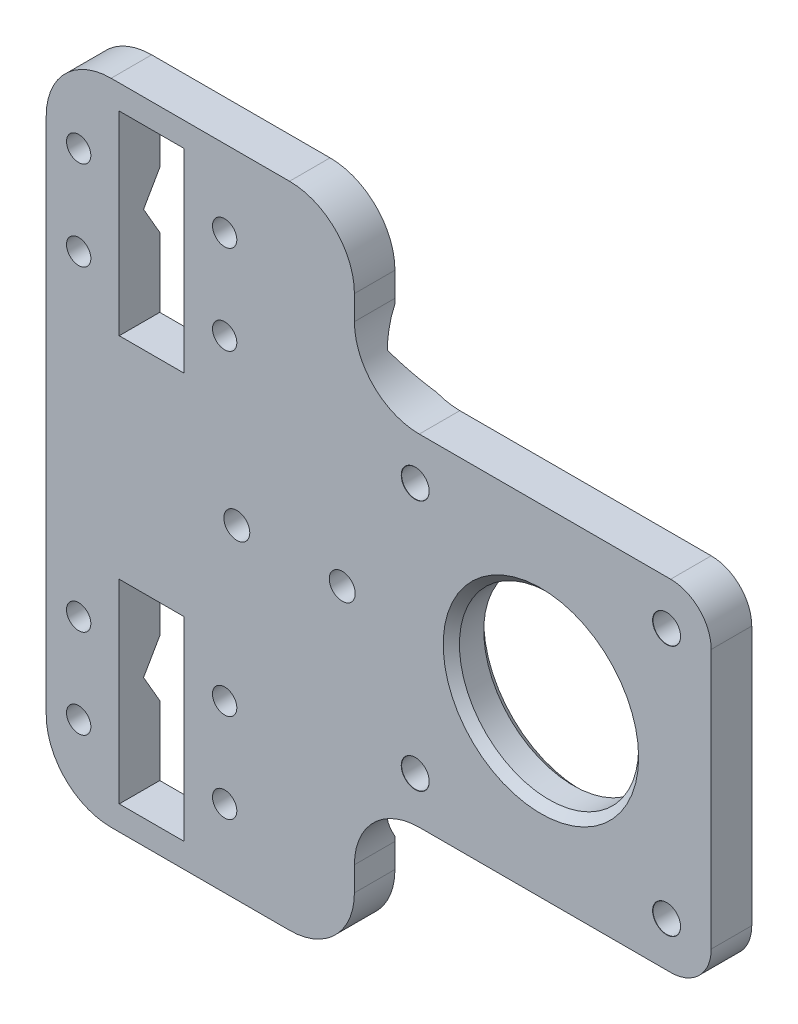
SolidWorks part; units mm, degrees
material "Liga 1060"
ref_plane "Plano frontal" through (0, 0, 0) normal (0, 0, 1) x (1, 0, 0)
ref_plane "Plano superior" through (0, 0, 0) normal (0, 1, 0) x (1, 0, 0)
ref_plane "Plano direito" through (0, 0, 0) normal (1, 0, 0) x (0, 0, -1)
sketch "Esboço1" plane through (0, 0, 0) normal (0, 0, 1) x (1, 0, 0)
  line L0 (0, 0) -> (41, 0) construction
  line L1 (-41, 40) -> (41, 40)
  line L2 (-41, 40) -> (-41, -40)
  line L3 (-41, -40) -> (41, -40)
  line L4 (41, 40) -> (41, -40)
  line L5 (-41, 40) -> (41, -40) construction
  line L6 (-41, -40) -> (41, 40) construction
  line L7 (-32, 37) -> (-24, 37)
  line L8 (-32, 37) -> (-32, 13)
  line L9 (-32, 13) -> (-24, 13)
  line L10 (-24, 37) -> (-24, 13)
  line L11 (-32, 37) -> (-24, 13) construction
  line L12 (-32, 13) -> (-24, 37) construction
  line L13 (-32, -13) -> (-24, -37) construction
  line L14 (-32, -37) -> (-24, -13) construction
  line L15 (-24, -37) -> (-24, -13)
  line L16 (-32, -13) -> (-24, -13)
  line L17 (-32, -37) -> (-32, -13)
  line L18 (-32, -37) -> (-24, -37)
  line L19 (-28, 25) -> (-32, 25) construction
  line L21 (-28, 25) -> (-28, 13) construction
  line L22 (-38.9278, 25) -> (-18.8884, 25) construction
  circle A0 centre (-37, 19.5) radius 1.5
  circle A1 centre (-37, -19.5) radius 1.5
  circle A2 centre (-19, -19.5) radius 1.5
  circle A3 centre (-19, 19.5) radius 1.5
  circle A4 centre (-19, 30.5) radius 1.5
  circle A5 centre (-37, 30.5) radius 1.5
  circle A6 centre (-37, -30.5) radius 1.5
  circle A7 centre (-19, -30.5) radius 1.5
  point P0 (0, 0)
  point P5 (-28, 25)
  point P17 (-28, -25)
  dimension "D7" = 3
  dimension "D8" = 9
  dimension "D9" = 5.5
  dimension "D1" = 80
  dimension "D2" = 82
  dimension "D3" = 8
  dimension "D4" = 24
  dimension "D5" = 25
  dimension "D6" = 13
extrude "Ressalto-extrusão1" add sketch "Esboço1" along normal blind 5
sketch "Esboço2" plane through (41, 0, 0) normal (1, 0, 0) x (0, 0, -1)
  line L0 (0, 25) -> (-2, 25) construction
  line L1 (0, -40) -> (0, 40) construction
  line L2 (-2, 25) -> (0, 28.4641)
  line L3 (0, 28.4641) -> (0, 21.5359)
  line L4 (-2, 25) -> (0, 21.5359)
  line L5 (0, 0) -> (-5, 0) construction
  line L6 (-5, -40) -> (-5, 40) construction
  line L7 (0, -25) -> (-2, -25) construction
  line L8 (-2, -25) -> (0, -21.5359)
  line L9 (0, -28.4641) -> (0, -21.5359)
  line L10 (-2, -25) -> (0, -28.4641)
  line L11 (0, 37) -> (0, 13) construction
  circle A0 centre (2.6188, 25) radius 4 construction
  point P17 (0, 0)
  point P20 (0, 25)
  dimension "D2" = 8
  dimension "D1" = 120
  dimension "D3" = 2
extrude "Corte-extrusão1" cut sketch "Esboço2" against normal through all
hole_wizard "Escareado para parafuso com cabeça escareada elevada de M31" positions "Esboço4" profile "Esboço3" countersink size "M3" standard "Din" end condition through all
sketch "Esboço4" plane through (0, 0, 0) normal (0, 0, -1) x (-1, 0, 0)
  line L7 (-35.5, 15.5) -> (-4.5, 15.5) construction
  line L10 (-4.5, 15.5) -> (-4.5, -15.5) construction
  line L11 (-4.5, -15.5) -> (-35.5, -15.5) construction
  line L12 (-35.5, -15.5) -> (-35.5, 15.5) construction
  line L14 (0, 0) -> (-35.5, 0) construction
  line L16 (-40, 20) -> (0, 20) construction
  line L17 (0, 20) -> (0, -20) construction
  line L18 (0, -20) -> (-40, -20) construction
  line L19 (-40, -20) -> (-40, 20) construction
  line L20 (-41, -40) -> (-41, 40) construction
  point P0 (-35.5, 15.5)
  point P20 (-4.5, 15.5)
  point P26 (-4.5, -15.5)
  point P28 (-35.5, -15.5)
  dimension "D1" = 31
  dimension "D2" = 4.5
  dimension "D3" = 1
sketch "Esboço3" plane through (35.5, 15.5, 0) normal (1, 0, 0) x (0, 1, 0)
  line L0 (0, 0) -> (0, 5)
  line L1 (0, 5) -> (1.725, 5)
  line L2 (1.7, 4.975) -> (1.7, 1.45)
  line L3 (1.7, 1.45) -> (3.15, 0)
  line L5 (3.15, 0) -> (0, 0)
  line L6 (-1.7, 1.45) -> (-3.15, 0) construction
  line L7 (1.725, 5) -> (1.7, 4.975)
  line L8 (-1.725, 5) -> (-1.7, 4.975) construction
  line L11 (0, -6.35) -> (0, 107.95) construction
  dimension "Thru Hole Dia." = 3.4
  dimension "Thru Hole Depth" = 5
  dimension "Near C'Sink Dia." = 6.3
  dimension "Near C'Sink Angle" = 90
  dimension "Far C'Sink Dia." = 3.45
  dimension "Far C'Sink Angle" = 90
sketch "Esboço5" plane through (0, 0, 5) normal (0, 0, 1) x (1, 0, 0)
  line L0 (4.5, 15.5) -> (35.5, -15.5) construction
  circle A0 centre (20, 0) radius 11.05
  dimension "D1" = 22.1
extrude "Corte-extrusão2" cut sketch "Esboço5" against normal through all
chamfer "Chanfro1" distance 1 angle 45 2 edges at (31.05, 0, 0) (31.05, 0, 5)
sketch "Esboço6" plane through (0, 0, 0) normal (0, 0, 1) x (1, 0, 0)
  line L0 (-41, 40) -> (-41, -40) construction
  line L1 (41, 40) -> (-3, 40)
  line L2 (41, 40) -> (41, 21)
  line L3 (41, 21) -> (-3, 21)
  line L4 (-3, 40) -> (-3, 21)
  line L5 (-41, 0) -> (0, 0) construction
  line L6 (-3, -40) -> (-3, -21)
  line L7 (41, -21) -> (-3, -21)
  line L8 (41, -40) -> (41, -21)
  line L9 (41, -40) -> (-3, -40)
  dimension "D1" = 38
  dimension "D2" = 42
extrude "Corte-extrusão3" cut sketch "Esboço6" along normal blind 10
fillet "Filete1" radius 8 6 edges at (-3, 21, 2.5) (-3, -21, 2.5) (-3, -40, 2.5) (-41, -40, 2.5) (-41, 40, 2.5) (-3, 40, 2.5)
fillet "Filete2" radius 5 2 edges at (41, -21, 2.5) (41, 21, 2.5)
sketch "Esboço7" plane through (0, 0, 0) normal (0, 0, 1) x (1, 0, 0)
  line L0 (-41, 0) -> (-11, 0) construction
  line L1 (-17.5, 0) -> (-11, 0) construction
  line L2 (-11, 0) -> (-11, 5.325) construction
  line L7 (-41, 32) -> (-41, -32) construction
  circle A0 centre (-17.5, 0) radius 1.6
  circle A1 centre (-4.5, 0) radius 1.6
  dimension "D1" = 3.2
  dimension "D2" = 13
  dimension "D3" = 30
extrude "Corte-extrusão5" cut sketch "Esboço7" along normal through all
